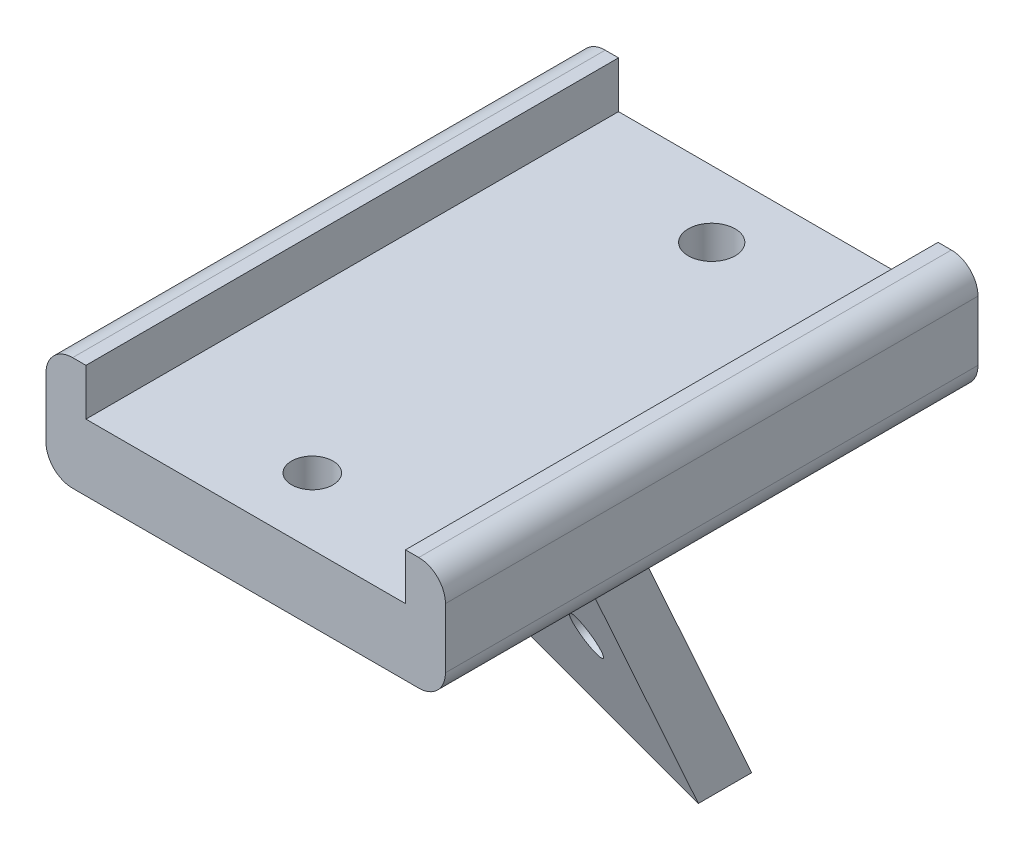
SolidWorks part; units mm, degrees
ref_plane "Front Plane" through (0, 0, 0) normal (0, 0, 1) x (1, 0, 0)
ref_plane "Top Plane" through (0, 0, 0) normal (0, 1, 0) x (1, 0, 0)
ref_plane "Right Plane" through (0, 0, 0) normal (1, 0, 0) x (0, 0, -1)
sketch "Sketch1" plane through (0, 0, 0) normal (0, 1, 0) x (1, 0, 0)
  line L1 (-11, -20) -> (11, -20)
  line L2 (-11, -20) -> (-11, 20)
  line L3 (-11, 20) -> (11, 20)
  line L4 (11, -20) -> (11, 20)
  line L5 (-11, -20) -> (11, 20) construction
  line L6 (-11, 20) -> (11, -20) construction
  circle A0 centre (0, 15) radius 1.7606
  circle A1 centre (0, -15) radius 1.5554
  point P0 (0, 0)
  dimension "D3" = 30
  dimension "D4" = 15
  dimension "D1" = 22
  dimension "D2" = 40
extrude "Boss-Extrude1" add sketch "Sketch1" along normal blind 5
sketch "Sketch2" plane through (0, 0, 0) normal (0, -1, 0) x (1, 0, 0)
  line L0 (-11, 0.1051) -> (11, 6)
  line L1 (-11, -20) -> (-11, 20) construction
  line L2 (11, 20) -> (11, -20) construction
  line L3 (11, 6) -> (11, 2)
  line L4 (11, 2) -> (-11, -3.8949)
  line L5 (-11, -3.8949) -> (-11, 0.1051)
  dimension "D1" = 4
  dimension "D2" = 14
  dimension "D3" = 105
sketch "Sketch4" plane through (0, 0, -20) normal (0, 0, -1) x (-1, 0, 0)
  line L0 (-11, 5) -> (-12, 5)
  line L1 (-12, 5) -> (-12, 8.5)
  line L2 (-12, 8.5) -> (-15, 8.5)
  line L3 (-15, 8.5) -> (-15, 0)
  line L4 (-15, 0) -> (-11, 0)
  line L5 (-11, 0) -> (-11, 5)
  line L6 (0, 0) -> (0, 5) construction
  line L7 (-11, 0) -> (11, 0) construction
  line L8 (-11, 5) -> (11, 5) construction
  line L9 (11, 0) -> (11, 5)
  line L10 (15, 0) -> (11, 0)
  line L11 (15, 8.5) -> (15, 0)
  line L12 (12, 8.5) -> (15, 8.5)
  line L13 (12, 5) -> (12, 8.5)
  line L14 (11, 5) -> (12, 5)
  dimension "D1" = 1
  dimension "D2" = 3.5
  dimension "D3" = 3
extrude "Boss-Extrude3" add sketch "Sketch4" against normal up to surface (40 mm away) up to face at (0, 2.5, 20)
fillet "Fillet1" radius 2 4 edges at (15, 0, 0) (-15, 0, 0) (-15, 8.5, 0) (15, 8.5, 0)
ref_plane "Plane1" through (0, -20, 0) normal (0, -1, 0) x (-1, 0, 0)
sketch "Sketch5" plane through (0, -20, 0) normal (0, -1, 0) x (-1, 0, 0)
  line L0 (-11, 3) -> (-11, 7)
  line L1 (-11, 7) -> (11, 12.8949)
  line L2 (11, 12.8949) -> (11, 8.8949)
  line L3 (11, 8.8949) -> (-11, 3)
  line L4 (-13, 20) -> (-13, -20) construction
  line L5 (13, -20) -> (13, 20) construction
  line L6 (13, -20) -> (-13, -20) construction
  dimension "D1" = 4
  dimension "D2" = 2
  dimension "D3" = 2
  dimension "D4" = 105
  dimension "D5" = 23
loft "Loft1" add profiles "Sketch2", "Sketch5"
ref_plane "Plane2" through (0.1992, 0.3346, -0.7435) normal (-0.2374, -0.3986, 0.8859) x (0.9714, -0.0974, 0.2165)
sketch "Sketch6" plane through (0.1992, 0.3346, -0.7435) normal (-0.2374, -0.3986, 0.8859) x (0.9714, -0.0974, 0.2165)
  line L0 (11.1185, 0.8207) -> (11.1185, -21.111) construction
  line L1 (-11.5287, -1.5983) -> (-11.5287, -23.53) construction
  line L2 (-11.5287, -1.5983) -> (11.1185, 0.8207) construction
  circle A0 centre (6.1185, -9.7702) radius 1.5
  circle A1 centre (-6.5287, -11.1211) radius 1.5
  point P6 (11.1185, -10.1451)
  dimension "D1" = 3
  dimension "D2" = 3
  dimension "D3" = 5
  dimension "D4" = 5
  dimension "D5" = 10
  dimension "D6" = 10
extrude "Cut-Extrude1" cut sketch "Sketch6" along normal up to surface (3.5434 mm away) up to face at (5.5, -5, 2.2763)
